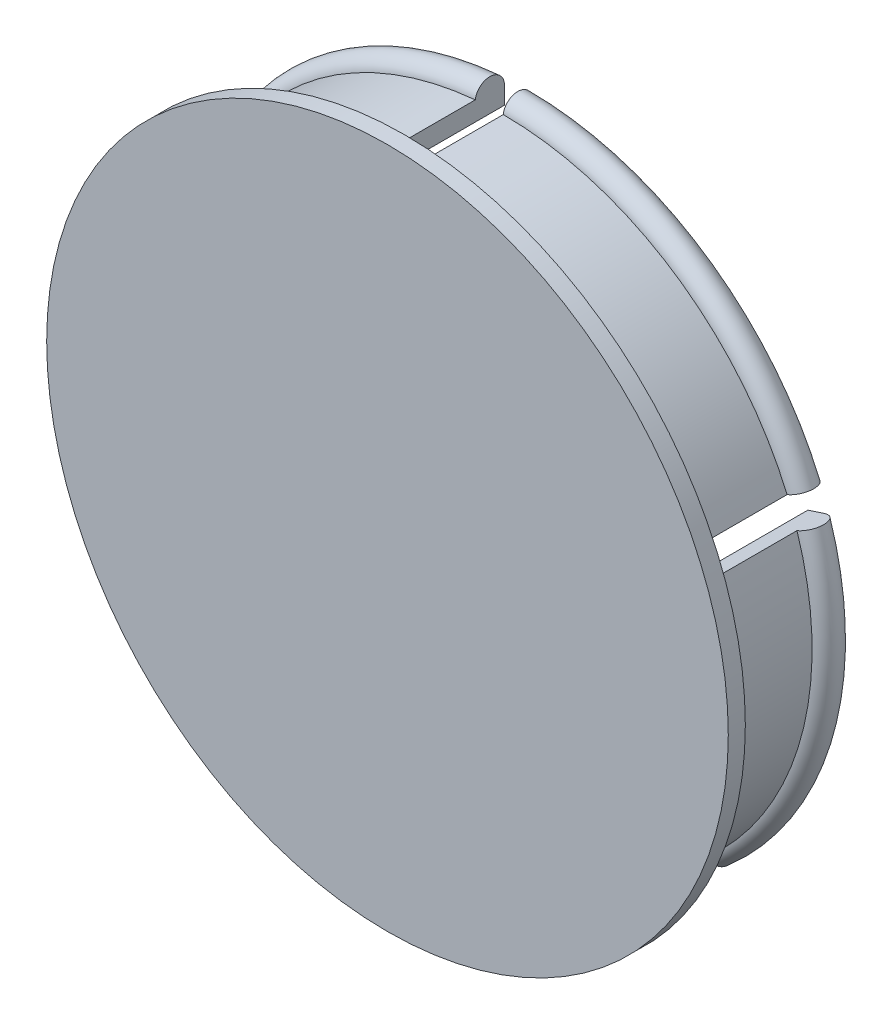
SolidWorks part; units mm, degrees
ref_plane "Front Plane" through (0, 0, 0) normal (0, 0, 1) x (1, 0, 0)
ref_plane "Top Plane" through (0, 0, 0) normal (0, 1, 0) x (1, 0, 0)
ref_plane "Right Plane" through (0, 0, 0) normal (1, 0, 0) x (0, 0, -1)
sketch "Esquisse1" plane through (0, 0, 0) normal (0, 0, 1) x (1, 0, 0)
  circle A0 centre (0, 0) radius 40
extrude "Boss.-Extru.1" add sketch "Esquisse1" along normal blind 2
sketch "Esquisse2" plane through (0, 0, 0) normal (0, 0, -1) x (-1, 0, 0)
  circle A0 centre (0, 0) radius 34
  circle A1 centre (0, 0) radius 36.25
extrude "Boss.-Extru.2" add sketch "Esquisse2" along normal blind 15
sketch "Esquisse3" plane through (0, 0, 0) normal (1, 0, 0) x (0, 0, -1)
  line L0 (0, -36.25) -> (15, -36.25) construction
  line L1 (15, -36.25) -> (11.5866, -36.25)
  line L2 (13.2933, -36.25) -> (13.2933, -37.75) construction
  arc A0 (15, -36.25) -> (11.5866, -36.25) centre (13.2933, -36.029) cw
  dimension "D1" = 1.5
sweep "Balayage1" add profiles "Esquisse3" path edge at (-36.25, 0, -15)
sketch "Esquisse6" plane through (0, 0, 0) normal (0, 0, -1) x (-1, 0, 0)
  line L0 (0, 34) -> (0, 93.8189)
  line L1 (0, 93.8189) -> (3.2862, 93.6497)
  line L2 (3.2862, 93.6497) -> (3.2862, 33.8408)
  line L3 (3.2862, 33.8408) -> (0, 34)
  circle A0 centre (0, 0) radius 34 construction
extrude "Enlèv. mat.-Extru.4" cut sketch "Esquisse6" along normal blind 25
pattern_circular "Répétition circulaire1" count 5 every 72 about axis through (0, 0, 0) along (0, 0, 1) of "Enlèv. mat.-Extru.4", "Boss.-Extru.1"
